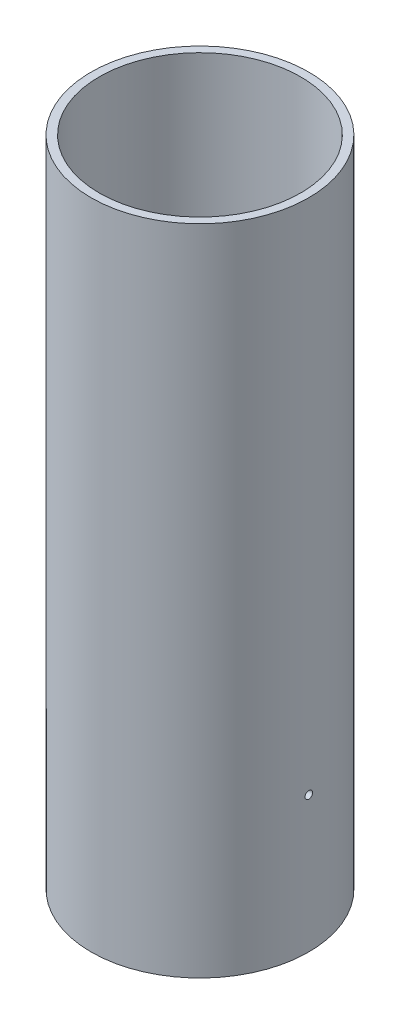
SolidWorks part; units mm, degrees
material "Glass"
ref_plane "Front Plane" through (0, 0, 0) normal (0, 0, 1) x (1, 0, 0)
ref_plane "Top Plane" through (0, 0, 0) normal (0, 1, 0) x (1, 0, 0)
ref_plane "Right Plane" through (0, 0, 0) normal (1, 0, 0) x (0, 0, -1)
sketch "Sketch1" plane through (0, 0, 0) normal (0, 1, 0) x (1, 0, 0)
  circle A0 centre (0, 0) radius 50.8
  circle A1 centre (0, 0) radius 46.99
  dimension "D1" = 101.6
  dimension "D2" = 93.98
extrude "Boss-Extrude1" add sketch "Sketch1" along normal blind 304.8
ref_plane "Plane1" through (50.8, 0, 0) normal (1, 0, 0) x (0, 0, -1)
sketch "Sketch2" plane through (50.8, 0, 0) normal (1, 0, 0) x (0, 0, -1)
  line L0 (-46.99, 0) -> (46.99, 0) construction
  circle A0 centre (0, 63.5) radius 1.7526
  dimension "D2" = 3.5052
  dimension "D1" = 63.5
extrude "Cut-Extrude1" cut sketch "Sketch2" against normal up to next
pattern_circular "CirPattern1" count 2 over 360 about axis through (0, 63.5, 0) along (1, 0, 0) of "Cut-Extrude1"
